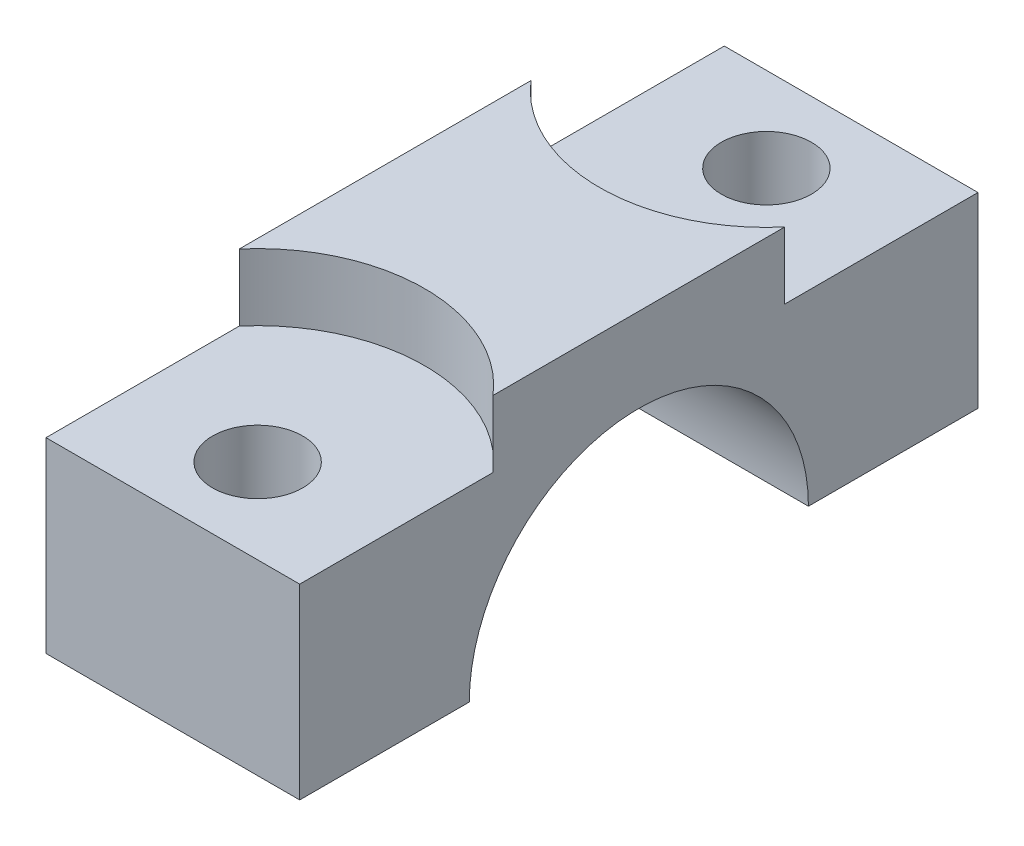
SolidWorks part; units mm, degrees
ref_plane "Front Plane" through (0, 0, 0) normal (0, 0, 1) x (1, 0, 0)
ref_plane "Top Plane" through (0, 0, 0) normal (0, 1, 0) x (1, 0, 0)
ref_plane "Right Plane" through (0, 0, 0) normal (1, 0, 0) x (0, 0, -1)
sketch "Sketch1" plane through (0, 0, 0) normal (1, 0, 0) x (0, 0, -1)
  line L0 (12.7, 0) -> (25.4, 0)
  line L1 (-25.4, 19) -> (25.4, 19)
  line L2 (-25.4, 19) -> (-25.4, 0)
  line L3 (-25.4, 0) -> (-12.7, 0)
  line L4 (25.4, 19) -> (25.4, 0)
  arc A0 (-12.7, 0) -> (12.7, 0) centre (0, 0) cw
  point P8 (-12.5039, 2.2229)
  dimension "D3" = 12.7
  dimension "D1" = 50.8
  dimension "D2" = 19
extrude "Boss-Extrude1" add sketch "Sketch1" along normal mid plane 19
sketch "Sketch2" plane through (0, 0, 0) normal (0, -1, 0) x (1, 0, 0)
  line L0 (-9.5, 19.05) -> (9.5, 19.05) construction
  line L1 (-9.5, 25.4) -> (-9.5, 12.7) construction
  line L2 (9.5, 25.4) -> (9.5, 12.7) construction
  line L3 (-9.5, -19.05) -> (9.5, -19.05) construction
  line L4 (-9.5, -12.7) -> (-9.5, -25.4) construction
  line L5 (9.5, -12.7) -> (9.5, -25.4) construction
  point P12 (0, 19.05)
  point P13 (0, -19.05)
hole_wizard "CBORE for M12 Hex Head Cap Screw1" positions "Sketch3" profile "Sketch4" counterbore size "M12" standard "ISO" end condition through all
sketch "Sketch3" plane through (0, 19, 0) normal (0, 1, 0) x (1, 0, 0)
  point P0 (0, 19.05)
  point P3 (0, -19.05)
sketch "Sketch4" plane through (0, 19, -19.05) normal (1, 0, 0) x (0, 0, 1)
  line L0 (0, 0) -> (0, 19)
  line L1 (0, 19) -> (3.375, 19)
  line L3 (3.375, 19) -> (3.375, 5)
  line L4 (3.375, 5) -> (12.5, 5)
  line L5 (12.5, 5) -> (12.5, 0)
  line L7 (12.5, 0) -> (0, 0)
  line L11 (0, -6.35) -> (0, 107.95) construction
  dimension "Thru Hole Dia." = 6.75
  dimension "Thru Hole Depth" = 19
  dimension "C'Bore Dia." = 25
  dimension "C'Bore Depth" = 5
